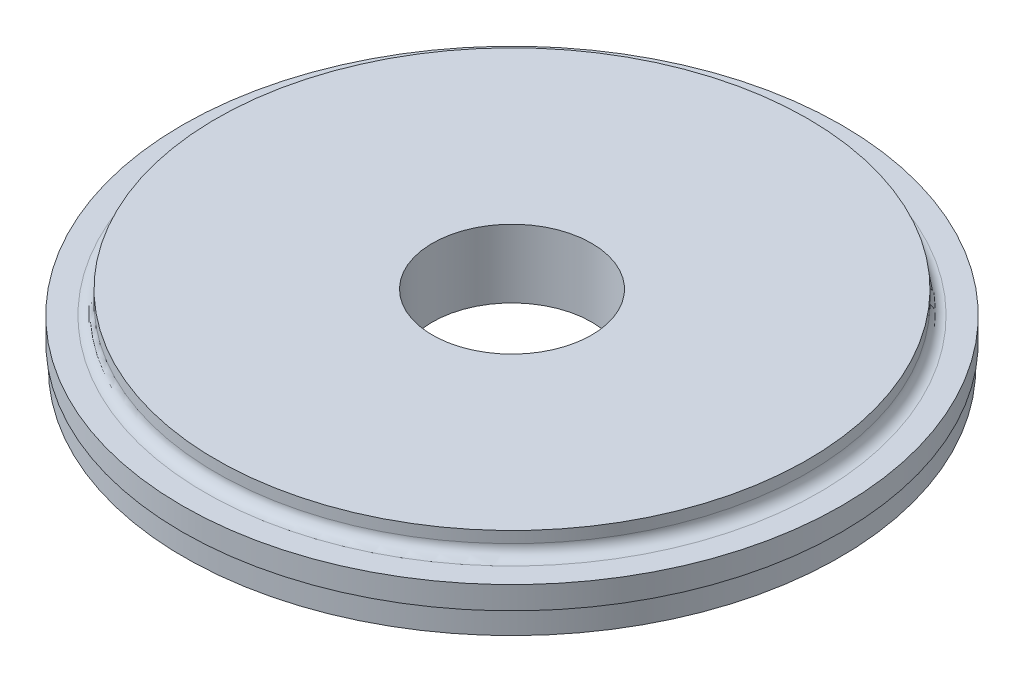
SolidWorks part; units mm, degrees
material "延性铁"
ref_plane "前视基准面" through (0, 0, 0) normal (0, 0, 1) x (1, 0, 0)
ref_plane "上视基准面" through (0, 0, 0) normal (0, 1, 0) x (1, 0, 0)
ref_plane "右视基准面" through (0, 0, 0) normal (1, 0, 0) x (0, 0, -1)
sketch "草图1" plane through (0, 0, 0) normal (1, 0, 0) x (0, 0, -1)
  line L0 (0, 0) -> (0, 38.8583) construction
  line L1 (-17.5, 15) -> (-17.5, 0)
  line L2 (-17.5, 0) -> (-72.1, 0)
  line L3 (-72.1, 0) -> (-72.1, 5)
  line L4 (-72.1, 5) -> (-72.5, 5)
  line L5 (-72.5, 5) -> (-72.5, 10)
  line L6 (-72.5, 10) -> (-67.5, 10)
  line L7 (-65, 12.5) -> (-65, 15)
  line L8 (-65, 15) -> (-17.5, 15)
  arc A0 (-67.5, 10) -> (-65, 12.5) centre (-67.5, 12.5) ccw
  point P13 (-65, 10)
  dimension "D8" = 2.5
  dimension "D1" = 35
  dimension "D2" = 145
  dimension "D3" = 144.2
  dimension "D4" = 130
  dimension "D5" = 5
  dimension "D6" = 5
  dimension "D7" = 15
revolve "旋转1" add sketch "草图1" angle 360 about L0
